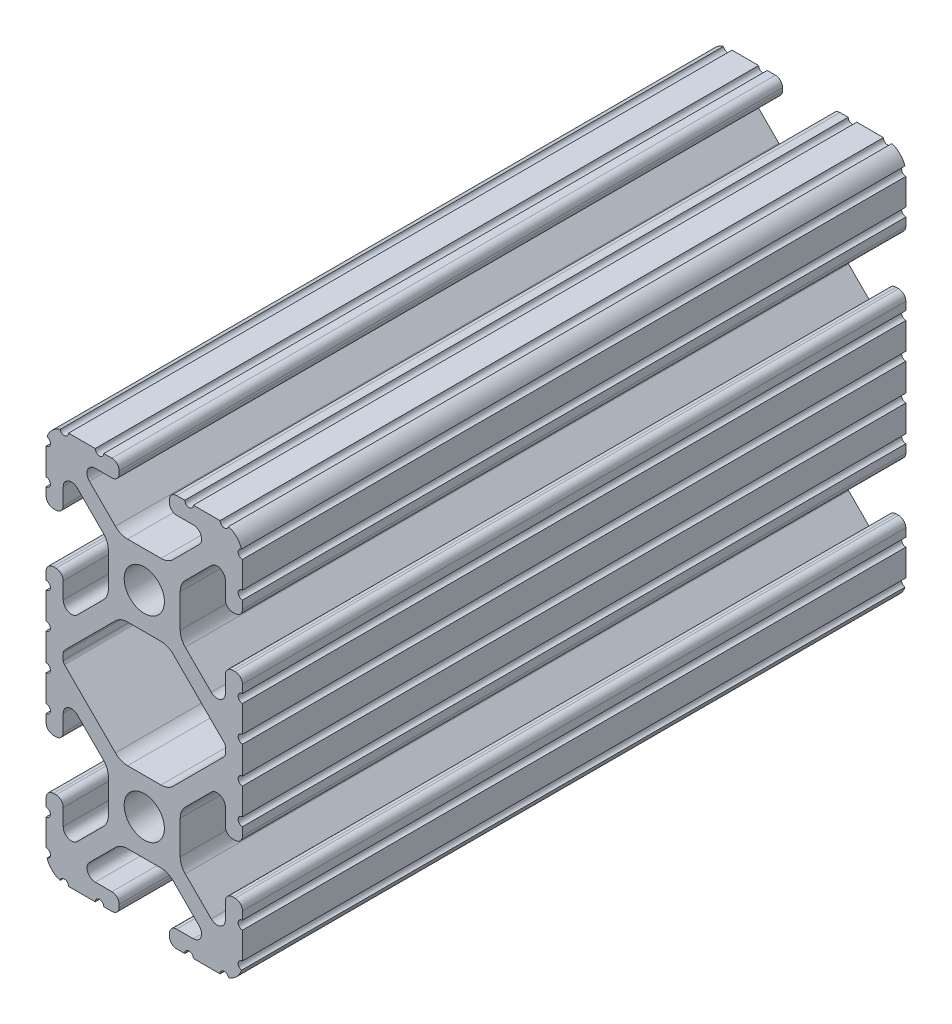
SolidWorks part; units mm, degrees
ref_plane "Front Plane" through (0, 0, 0) normal (0, 0, 1) x (1, 0, 0)
ref_plane "Top Plane" through (0, 0, 0) normal (0, 1, 0) x (1, 0, 0)
ref_plane "Right Plane" through (0, 0, 0) normal (1, 0, 0) x (0, 0, -1)
sketch "Sketch2" plane through (0, 0, 0) normal (0, 0, 1) x (1, 0, 0)
  line L0 (0, 25.4) -> (0, -25.4) construction
  line L1 (-12.7, 0) -> (12.7, 0) construction
  line L2 (3.2512, -25.4) -> (12.7, -25.4)
  line L3 (12.7, -25.4) -> (12.7, -15.9512)
  line L4 (3.2512, -25.4) -> (3.2512, -23.1902)
  line L5 (3.2512, -23.1902) -> (8.9276, -23.1902)
  line L6 (8.9276, -23.1902) -> (3.0856, -17.3482)
  line L7 (0, -12.7) -> (12.7, -25.4) construction
  line L8 (12.7, -15.9512) -> (10.4902, -15.9512)
  line L9 (10.4902, -15.9512) -> (10.4902, -21.6276)
  line L10 (10.4902, -21.6276) -> (4.6482, -15.7856)
  circle A0 centre (0, -12.7) radius 2.6035
  arc A1 (6.3485, -23.1902) -> (7.1039, -21.3665) centre (6.3485, -22.1219) ccw construction
  point P8 (0, -17.3482)
  dimension "Center Hole Diameter" = 5.207
  dimension "Rail Height" = 50.8
  dimension "Rail Width" = 25.4
  dimension "T-Slot Width" = 6.5024
  dimension "Slot Inner Width" = 14.8336
  dimension "Thickness" = 2.2098
  dimension "Slot Depth" = 5.842
  dimension "D1" = 2.2098
  dimension "C to C" = 25.4
sketch "Sketch3" plane through (0, 0, 0) normal (1, 0, 0) x (0, 0, -1)
  line L0 (-76.2, -25.4) -> (76.2, -25.4) construction
  line L1 (-50.8, 0) -> (50.8, 0) construction
  dimension "Length" = 152.4
  dimension "D1" = 25.4
sketch "Sketch4" plane through (0, 0, 0) normal (0, 0, 1) x (1, 0, 0)
  line L0 (4.1904, -25.4) -> (10.1173, -25.4)
  line L1 (3.2512, -25.4) -> (12.7, -25.4) construction
  line L2 (3.2512, -25.4) -> (3.2512, -23.1902) construction
  line L3 (3.2512, -23.1902) -> (8.9276, -23.1902) construction
  line L4 (3.2512, -24.1294) -> (3.2512, -24.4608)
  line L5 (4.1904, -23.1902) -> (6.3485, -23.1902)
  line L6 (0, -17.3482) -> (2.164, -17.3482)
  line L7 (8.9276, -23.1902) -> (3.0856, -17.3482) construction
  line L8 (3.7373, -17.9999) -> (7.1039, -21.3665)
  line L9 (12.7, -25.4) -> (12.7, -15.9512) construction
  line L10 (10.4902, -21.6276) -> (4.6482, -15.7856) construction
  line L11 (10.4902, -15.9512) -> (10.4902, -21.6276) construction
  line L12 (10.4902, -19.0485) -> (10.4902, -16.8904)
  line L13 (12.7, -15.9512) -> (10.4902, -15.9512) construction
  line L14 (11.4294, -15.9512) -> (11.7608, -15.9512)
  line L15 (12.7, -16.8904) -> (12.7, -22.8173)
  line L16 (8.6665, -19.8039) -> (5.2999, -16.4373)
  line L17 (4.6482, -12.7) -> (4.6482, -14.864)
  line L19 (0, -17.3482) -> (0, -15.3035)
  line L20 (0, 25.4) -> (0, -25.4) construction
  line L21 (4.6482, -12.7) -> (2.6035, -12.7)
  arc A0 (3.2512, -24.4608) -> (4.1904, -25.4) centre (4.1904, -24.4608) ccw
  circle A1 centre (0, -12.7) radius 2.6035 construction
  arc A2 (3.2512, -24.1294) -> (4.1904, -23.1902) centre (4.1904, -24.1294) cw
  arc A3 (6.3485, -23.1902) -> (7.1039, -21.3665) centre (6.3485, -22.1219) ccw
  arc A4 (2.164, -17.3482) -> (3.7373, -17.9999) centre (2.164, -19.5732) cw
  arc A5 (10.1173, -25.4) -> (12.7, -22.8173) centre (10.1173, -22.8173) ccw
  arc A6 (8.6665, -19.8039) -> (10.4902, -19.0485) centre (9.4219, -19.0485) ccw
  arc A7 (10.4902, -16.8904) -> (11.4294, -15.9512) centre (11.4294, -16.8904) cw
  arc A8 (11.7608, -15.9512) -> (12.7, -16.8904) centre (11.7608, -16.8904) cw
  arc A9 (5.2999, -16.4373) -> (4.6482, -14.864) centre (6.8732, -14.864) cw
  arc A11 (0, -15.3035) -> (2.6035, -12.7) centre (0, -12.7) ccw
  dimension "D1" = 2.5827
  dimension "D2" = 2.225
  dimension "D3" = 0.9392
extrude "Boss-Extrude1" add sketch "Sketch4" along normal mid plane 152.4
sketch "Sketch5" plane through (0, 0, 0) normal (0, 0, 1) x (1, 0, 0)
  line L0 (3.2512, -25.4) -> (12.7, -25.4) construction
  line L1 (4.1904, -23.1902) -> (6.3485, -23.1902) construction
  line L3 (0, -12.7) -> (12.7, -25.4) construction
  line L4 (6.3485, -23.1902) -> (6.3485, -25.4) construction
  line L5 (8.9276, -23.1902) -> (3.0856, -17.3482) construction
  circle A0 centre (10.3562, -25.4) radius 0.5524
  circle A1 centre (5.796, -25.4) radius 0.5524
  circle A2 centre (12.7, -23.0562) radius 0.5524
  circle A3 centre (12.7, -18.496) radius 0.5524
  point P10 (5.2694, -23.1902)
  point P12 (9.4219, -19.0485)
  dimension "D1" = 1.1049
extrude "Cut-Extrude1" cut sketch "Sketch5" against normal through all both and the other way through all
mirror "Mirror1" about plane through (4.6482, -12.7, 76.2) normal (0, -1, 0) of bodies 137 134
sketch "Sketch6" plane through (0, 0, 0) normal (0, 0, 1) x (1, 0, 0)
  line L0 (12.7, -1.7914) -> (12.7, 0)
  line L1 (12.7, 0) -> (9.8037, 0)
  line L2 (-12.7, 0) -> (12.7, 0) construction
  line L3 (9.8037, 0) -> (9.8037, -2.3438)
  line L4 (9.8037, -2.3438) -> (12.1476, -2.3438)
  circle A0 centre (12.7, -2.3438) radius 0.5524 construction
  arc A1 (12.7, -1.7914) -> (12.1476, -2.3438) centre (12.7, -2.3438) ccw
  arc A4 (12.58, -1.8046) -> (12.7, -2.8963) centre (12.7, -2.3438) ccw construction
  arc A6 (9.8037, 0) -> (10.8954, -0.12) centre (10.3562, 0) ccw construction
extrude "Boss-Extrude2" add sketch "Sketch6" along normal mid plane 152.4
sketch "Sketch7" plane through (0, 0, 0) normal (0, 0, 1) x (1, 0, 0)
  line L0 (5.4206, -5.7168) -> (10.3284, -0.809)
  line L1 (3.7373, -7.4001) -> (7.1039, -4.0335) construction
  line L2 (10.4902, -0.4184) -> (10.4902, 0)
  line L3 (0, 0) -> (10.4902, 0)
  line L4 (-12.7, 0) -> (12.7, 0) construction
  line L5 (0, 0) -> (5.4206, -5.7168)
  arc A0 (10.3284, -0.809) -> (10.4902, -0.4184) centre (9.9377, -0.4184) ccw
  arc A3 (12.7, -1.7914) -> (12.7, -2.8963) centre (12.7, -2.3438) ccw construction
extrude "Cut-Extrude2" cut sketch "Sketch7" against normal through all both and the other way through all
mirror "Mirror2" about plane through (0, 0, 0) normal (0, 1, 0) of bodies 139 135
mirror "Mirror3" about plane through (0, 0, 0) normal (1, 0, 0) of bodies 136
sketch "Sketch8" plane through (0, 0, -76.2) normal (0, 0, -1) x (-1, 0, 0)
  line L1 (-24.2228, 32.1699) -> (24.2228, 32.1699)
  line L2 (-24.2228, 32.1699) -> (-24.2228, -32.1699)
  line L3 (-24.2228, -32.1699) -> (24.2228, -32.1699)
  line L4 (24.2228, 32.1699) -> (24.2228, -32.1699)
  line L5 (-24.2228, 32.1699) -> (24.2228, -32.1699) construction
  line L6 (-24.2228, -32.1699) -> (24.2228, 32.1699) construction
  point P0 (0, 0)
extrude "Cut-Extrude3" cut sketch "Sketch8" against normal blind 66.548
equation "\"D1@Boss-Extrude1\"=\"Length@Sketch3\""
equation "\"D1@Sketch2\"=\"Thickness@Sketch2\""
equation "\"D2@Sketch4\"=\"Slot Inner Width@Sketch2\"*0.15"
equation "\"D1@Sketch4\"=\"D3@Sketch4\"*2.75"
equation "\"D3@Sketch4\"=\"Thickness@Sketch2\"*0.425"
equation "\"D1@Sketch5\"=\"Thickness@Sketch2\"*0.5"
equation "\"D1@Boss-Extrude2\"=\"Length@Sketch3\""
